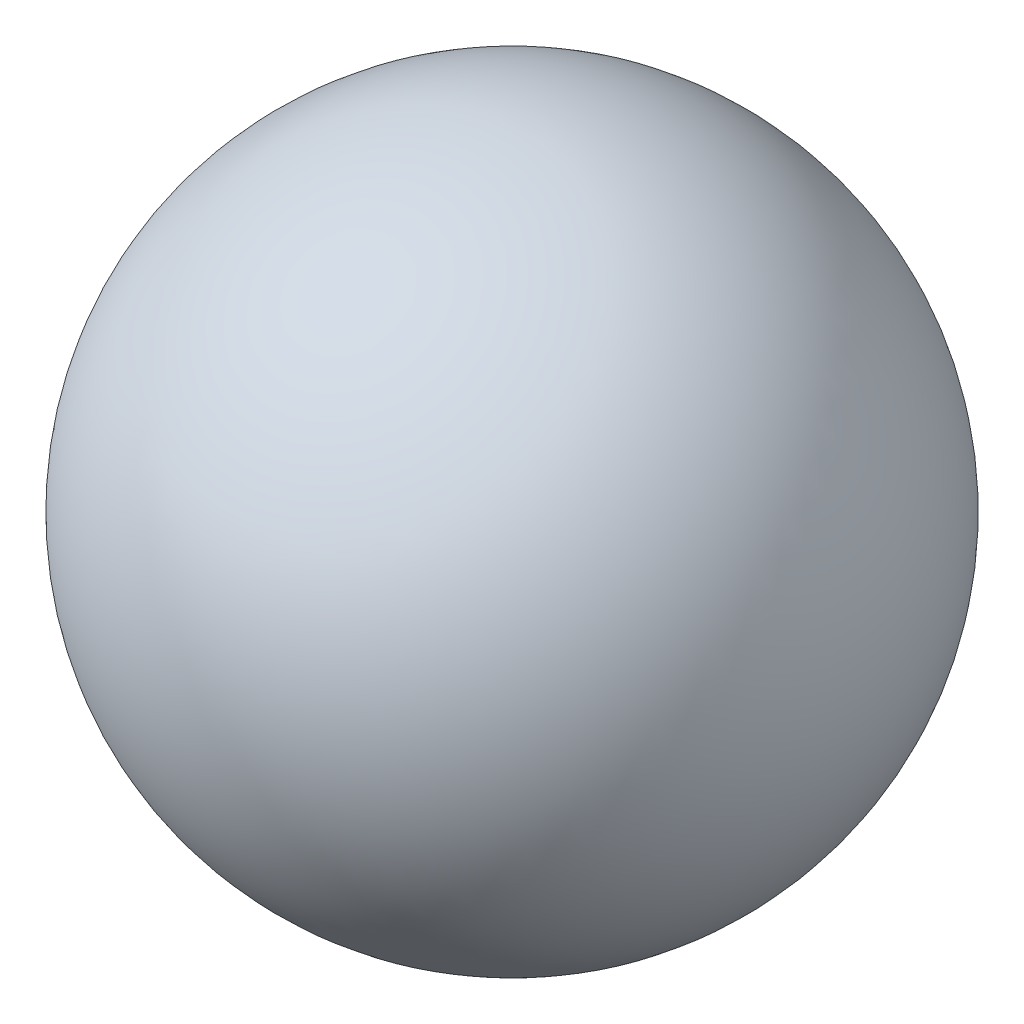
SolidWorks part; units mm, degrees
ref_plane "Front Plane" through (0, 0, 0) normal (0, 0, 1) x (1, 0, 0)
ref_plane "Top Plane" through (0, 0, 0) normal (0, 1, 0) x (1, 0, 0)
ref_plane "Right Plane" through (0, 0, 0) normal (1, 0, 0) x (0, 0, -1)
sketch "Sketch1" plane through (0, 0, 0) normal (1, 0, 0) x (0, 0, -1)
  line L0 (0, -5) -> (0, 5)
  arc A0 (0, -5) -> (0, 5) centre (0, 0) ccw
  dimension "D1" = 10
revolve "Revolve1" add sketch "Sketch1" angle 360 about L0
scale "Scale1" scale about centroid uniform scaling yes scale factor 0.266667
